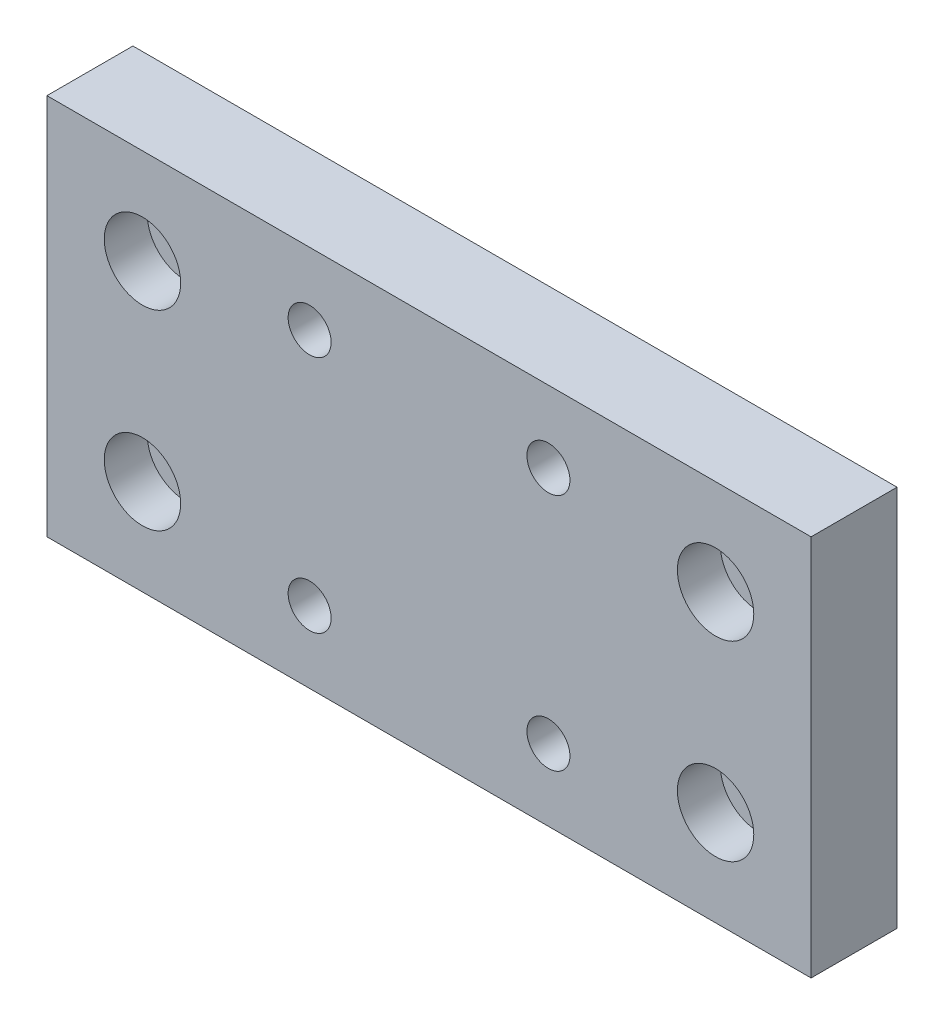
SolidWorks part; units mm, degrees
ref_plane "前视基准面" through (0, 0, 0) normal (0, 0, 1) x (1, 0, 0)
ref_plane "上视基准面" through (0, 0, 0) normal (0, 1, 0) x (1, 0, 0)
ref_plane "右视基准面" through (0, 0, 0) normal (1, 0, 0) x (0, 0, -1)
sketch "草图1" plane through (0, 0, 0) normal (0, 0, 1) x (1, 0, 0)
  line L1 (-40, 20) -> (40, 20)
  line L2 (-40, 20) -> (-40, -20)
  line L3 (-40, -20) -> (40, -20)
  line L4 (40, 20) -> (40, -20)
  line L5 (-40, 20) -> (40, -20) construction
  line L6 (-40, -20) -> (40, 20) construction
  point P0 (0, 0)
  dimension "D1" = 40
  dimension "D2" = 80
extrude "凸台-拉伸1" add sketch "草图1" along normal blind 9
sketch "草图2" plane through (0, 0, 0) normal (0, 0, -1) x (-1, 0, 0)
  line L0 (-40, 20) -> (40, 20) construction
  line L1 (40, 20) -> (40, -20) construction
  line L2 (40, -20) -> (-40, -20) construction
  circle A0 centre (30, 10) radius 2.25
  circle A1 centre (30, -10) radius 2.25
  point P4 (0, 0)
  point P9 (31.7056, 20)
  point P10 (35.9603, 9.978)
  dimension "D1" = 4.5
  dimension "D2" = 4.5
  dimension "D6" = 10
  dimension "D3" = 10
  dimension "D4" = 10
  dimension "D5" = 10
extrude "切除-拉伸1" cut sketch "草图2" against normal through all
mirror "镜向1" about plane through (0, 0, 0) normal (1, 0, 0) of "切除-拉伸1"
sketch "草图3" plane through (0, 0, 0) normal (0, 0, -1) x (-1, 0, 0)
  line L0 (40, -20) -> (-40, -20) construction
  line L1 (40, 20) -> (40, -20) construction
  line L2 (-40, 20) -> (40, 20) construction
  circle A0 centre (12.5, -12.5) radius 2.25
  circle A1 centre (12.5, 12.5) radius 2.25
  dimension "D1" = 7.5
  dimension "D2" = 27.5
  dimension "D3" = 4.5
  dimension "D4" = 7.5
  dimension "D5" = 4.5
  dimension "D6" = 27.5
extrude "切除-拉伸2" cut sketch "草图3" against normal blind 9
mirror "镜向2" about plane through (0, 0, 0) normal (1, 0, 0) of "切除-拉伸2"
sketch "草图4" plane through (0, 0, 0) normal (0, 0, -1) x (-1, 0, 0)
  circle A0 centre (12.5, 12.5) radius 4
  circle A1 centre (12.5, -12.5) radius 4
  circle A2 centre (-12.5, 12.5) radius 4
  circle A3 centre (-12.5, -12.5) radius 4
  dimension "D1" = 8
  dimension "D2" = 8
  dimension "D3" = 8
  dimension "D4" = 8
extrude "切除-拉伸3" cut sketch "草图4" against normal blind 4.5
sketch "草图6" plane through (0, 0, 9) normal (0, 0, 1) x (1, 0, 0)
  circle A0 centre (-30, -10) radius 4
  circle A1 centre (-30, 10) radius 4
  circle A2 centre (30, -10) radius 4
  circle A3 centre (30, 10) radius 4
  dimension "D1" = 8
  dimension "D2" = 8
  dimension "D3" = 8
  dimension "D4" = 8
extrude "切除-拉伸5" cut sketch "草图6" against normal blind 4.5
